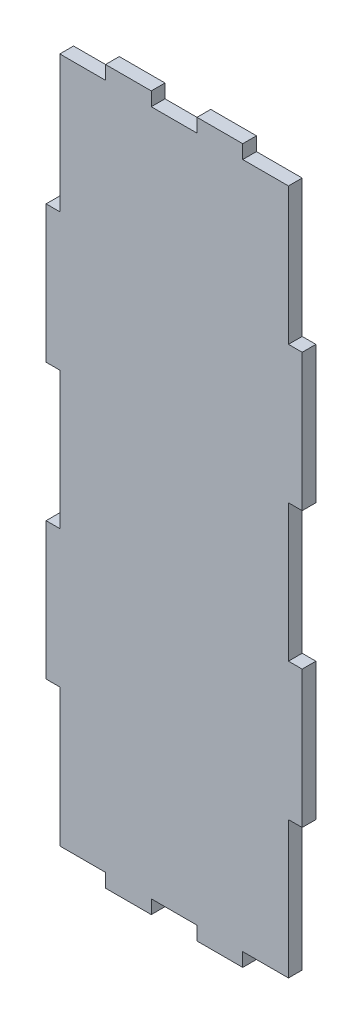
SolidWorks part; units mm, degrees
material "Pinho"
ref_plane "Plano frontal" through (0, 0, 0) normal (0, 0, 1) x (1, 0, 0)
ref_plane "Plano superior" through (0, 0, 0) normal (0, 1, 0) x (1, 0, 0)
ref_plane "Plano direito" through (0, 0, 0) normal (1, 0, 0) x (0, 0, -1)
sketch "Esboço1" plane through (0, 0, 0) normal (0, 0, 1) x (1, 0, 0)
  line L0 (-10, -20.5678) -> (-10, -50.5678)
  line L2 (-10, 39.322) -> (-10, 9.4322)
  line L4 (40, 39.322) -> (40, 9.322)
  line L5 (-10, -80.5678) -> (-10, -110.678)
  line L6 (-10, -20.5678) -> (-13, -20.5678)
  line L9 (-10, 9.4322) -> (-13, 9.4322)
  line L10 (-13, -20.5678) -> (-13, 9.4322)
  line L13 (-13, -80.5678) -> (-10, -80.5678)
  line L14 (-13, -80.5678) -> (-13, -50.5678)
  line L15 (-13, -50.5678) -> (-10, -50.5678)
  line L27 (40, -80.678) -> (40, -110.678)
  line L28 (40, -20.678) -> (43, -20.678)
  line L30 (40, 9.322) -> (43, 9.322)
  line L31 (43, -20.678) -> (43, 9.322)
  line L34 (40, -80.678) -> (43, -80.678)
  line L36 (40, -50.678) -> (43, -50.678)
  line L37 (43, -80.678) -> (43, -50.678)
  line L38 (40, -20.678) -> (40, -50.678)
  line L81 (30, 42.322) -> (30, 39.322)
  line L83 (20, 39.322) -> (20, 42.322)
  line L85 (10, 42.322) -> (10, 39.322)
  line L87 (0, 39.322) -> (0, 42.322)
  line L94 (30, -113.678) -> (30, -110.678)
  line L96 (20, -110.678) -> (20, -113.678)
  line L98 (10, -113.678) -> (10, -110.678)
  line L100 (0, -110.678) -> (0, -113.678)
  line L103 (30, 42.322) -> (20, 42.322)
  line L104 (10, 42.322) -> (0, 42.322)
  line L105 (0, 39.322) -> (-10, 39.322)
  line L106 (10, 39.322) -> (20, 39.322)
  line L107 (30, 39.322) -> (40, 39.322)
  line L108 (40, -110.678) -> (30, -110.678)
  line L109 (20, -110.678) -> (10, -110.678)
  line L110 (0, -110.678) -> (-10, -110.678)
  line L111 (0, -113.678) -> (10, -113.678)
  line L112 (20, -113.678) -> (30, -113.678)
  point P0 (0, 0)
  dimension "D1" = 150
  dimension "D3" = 30
  dimension "D4" = 30
  dimension "D6" = 30
  dimension "D7" = 3
  dimension "D8" = 3
  dimension "D9" = 3
  dimension "D10" = 30
  dimension "D11" = 30
  dimension "D12" = 30
  dimension "D13" = 30
  dimension "D21" = 3
  dimension "D22" = 3
  dimension "D28" = 3
  dimension "D29" = 3
extrude "Ressalto-extrusão1" add sketch "Esboço1" along normal blind 3
